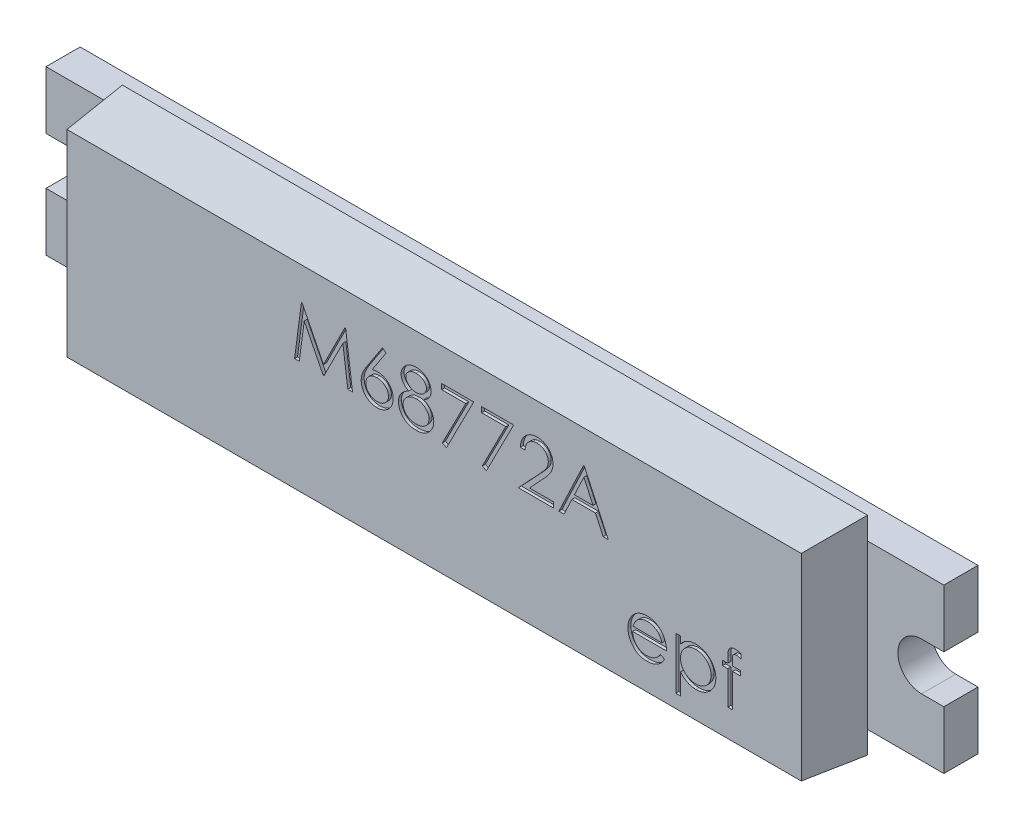
SolidWorks part; units mm, degrees
ref_plane "Alzado" through (0, 0, 0) normal (0, 0, 1) x (1, 0, 0)
ref_plane "Planta" through (0, 0, 0) normal (0, 1, 0) x (1, 0, 0)
ref_plane "Vista lateral" through (0, 0, 0) normal (1, 0, 0) x (0, 0, -1)
sketch "Croquis1" plane through (0, 0, 0) normal (0, 0, 1) x (1, 0, 0)
  line L1 (-30.25, -5.5) -> (30.25, -5.5)
  line L2 (-30.25, -5.5) -> (-30.25, 5.5)
  line L3 (-30.25, 5.5) -> (30.25, 5.5)
  line L4 (30.25, -5.5) -> (30.25, 5.5)
  line L5 (-30.25, -5.5) -> (30.25, 5.5) construction
  line L6 (-30.25, 5.5) -> (30.25, -5.5) construction
  point P0 (0, 0)
  dimension "D1" = 60.5
  dimension "D2" = 11
extrude "Saliente-Extruir1" add sketch "Croquis1" along normal blind 2.3
sketch "Croquis2" plane through (0, 0, 2.3) normal (0, 0, 1) x (1, 0, 0)
  line L0 (-38.0446, 0) -> (40.7787, 0) construction
  line L2 (-28.75, 1.6) -> (-31.5698, 1.6)
  line L3 (-28.75, -1.6) -> (-31.5698, -1.6)
  line L4 (-31.5698, 1.6) -> (-31.5698, -1.6)
  line L6 (28.75, 1.6) -> (32.3574, 1.6)
  line L7 (28.75, -1.6) -> (32.3574, -1.6)
  line L8 (32.3574, 1.6) -> (32.3574, -1.6)
  arc A0 (-28.75, -1.6) -> (-28.75, 1.6) centre (-28.75, 0) ccw
  arc A1 (28.75, 1.6) -> (28.75, -1.6) centre (28.75, 0) ccw
  dimension "D1" = 3.2
  dimension "D3" = 3.2
  dimension "D2" = 28.75
  dimension "D4" = 28.75
  dimension "D5" = 2.8198
  dimension "D6" = 3.6074
  dimension "D7" = 3.2
  dimension "D8" = 3.2
extrude "Cortar-Extruir1" cut sketch "Croquis2" against normal up to next
sketch "Croquis3" plane through (0, 0, 2.3) normal (0, 0, 1) x (1, 0, 0)
  line L1 (25.1, -7) -> (-25.1, -7)
  line L2 (25.1, -7) -> (25.1, 7)
  line L3 (25.1, 7) -> (-25.1, 7)
  line L4 (-25.1, -7) -> (-25.1, 7)
  line L5 (25.1, -7) -> (-25.1, 7) construction
  line L6 (25.1, 7) -> (-25.1, -7) construction
  point P0 (0, 0)
  dimension "D1" = 50.2
  dimension "D2" = 14
extrude "Saliente-Extruir2" add sketch "Croquis3" along normal blind 4.1 draft 5
sketch "Croquis6" plane through (-30.25, 0, 0) normal (-1, 0, 0) x (0, 0, 1)
  line L0 (0, 0) -> (0, -10) construction
  line L1 (0, 0) -> (3.4, 0) construction
  line L2 (0, -9) -> (0.2, -9) construction
  line L3 (0, -10) -> (0.2, -10)
  line L4 (0, -10) -> (0, -9)
  line L5 (3.4, -8) -> (3.6, -8) construction
  line L6 (0.2, -10) -> (0.2, -9.0748)
  line L7 (3.4, 0) -> (3.6, 0)
  line L8 (3.4, 0) -> (3.4, -7.9252)
  line L9 (3.4, -7.9252) -> (0.0718, -8.9041)
  line L10 (3.6, 0) -> (3.6, -8)
  line L11 (3.5282, -8.0959) -> (0.2, -9.0748)
  arc A0 (0.0718, -8.9041) -> (0, -9) centre (0.1, -9) ccw
  arc A1 (3.5282, -8.0959) -> (3.6, -8) centre (3.5, -8) ccw
  dimension "D1" = 3.4
  dimension "D2" = 10
  dimension "D3" = 0.2
  dimension "D4" = 1
  dimension "D5" = 8
  dimension "D6" = 0.2
extrude "Saliente-Extruir3" add sketch "Croquis6" along normal blind 0.2 from offset 8.3 offset against normal yes
sketch "Croquis7" plane through (-30.25, 0, 0) normal (-1, 0, 0) x (0, 0, 1)
  line L8 (3.6, -6.8863) -> (3.4, -6.9038)
  line L9 (3.4, -6.9038) -> (3.4, -7.9252)
  line L10 (3.4, -7.9252) -> (0.0718, -8.9041)
  line L11 (0, -9) -> (0, -10)
  line L12 (0, -10) -> (0.2, -10)
  line L13 (0.2, -10) -> (0.2, -9.0748)
  line L14 (0.2, -9.0748) -> (3.5282, -8.0959)
  line L15 (3.6, -8) -> (3.6, -6.8863)
  line L16 (3.6, -6.8863) -> (3.4, -6.9038)
  line L17 (3.4, -6.9038) -> (3.4, -7.9252)
  line L18 (3.4, -7.9252) -> (0.0718, -8.9041)
  line L19 (0, -9) -> (0, -10)
  line L20 (0, -10) -> (0.2, -10)
  line L21 (0.2, -10) -> (0.2, -9.0748)
  line L22 (0.2, -9.0748) -> (3.5282, -8.0959)
  line L23 (3.6, -8) -> (3.6, -6.8863)
  arc A2 (0.0718, -8.9041) -> (0, -9) centre (0.1, -9) ccw
  arc A3 (3.5282, -8.0959) -> (3.6, -8) centre (3.5, -8) ccw
  arc A4 (0.0718, -8.9041) -> (0, -9) centre (0.1, -9) ccw
  arc A5 (3.5282, -8.0959) -> (3.6, -8) centre (3.5, -8) ccw
  dimension "D1" = 0
extrude "Saliente-Extruir4" add sketch "Croquis7" along normal blind 0.2 from offset 21.3 offset against normal yes
sketch "Croquis8" plane through (-30.25, 0, 0) normal (-1, 0, 0) x (0, 0, 1)
  line L8 (3.6, -6.8863) -> (3.4, -6.9038)
  line L9 (3.4, -6.9038) -> (3.4, -7.9252)
  line L10 (3.4, -7.9252) -> (0.0718, -8.9041)
  line L11 (0, -9) -> (0, -10)
  line L12 (0, -10) -> (0.2, -10)
  line L13 (0.2, -10) -> (0.2, -9.0748)
  line L14 (0.2, -9.0748) -> (3.5282, -8.0959)
  line L15 (3.6, -8) -> (3.6, -6.8863)
  line L16 (3.6, -6.8863) -> (3.4, -6.9038)
  line L17 (3.4, -6.9038) -> (3.4, -7.9252)
  line L18 (3.4, -7.9252) -> (0.0718, -8.9041)
  line L19 (0, -9) -> (0, -10)
  line L20 (0, -10) -> (0.2, -10)
  line L21 (0.2, -10) -> (0.2, -9.0748)
  line L22 (0.2, -9.0748) -> (3.5282, -8.0959)
  line L23 (3.6, -8) -> (3.6, -6.8863)
  arc A2 (0.0718, -8.9041) -> (0, -9) centre (0.1, -9) ccw
  arc A3 (3.5282, -8.0959) -> (3.6, -8) centre (3.5, -8) ccw
  arc A4 (0.0718, -8.9041) -> (0, -9) centre (0.1, -9) ccw
  arc A5 (3.5282, -8.0959) -> (3.6, -8) centre (3.5, -8) ccw
  dimension "D1" = 0
extrude "Saliente-Extruir5" add sketch "Croquis8" along normal blind 0.2 from offset 43.3 offset against normal yes
sketch "Croquis9" plane through (-30.25, 0, 0) normal (-1, 0, 0) x (0, 0, 1)
  line L8 (3.6, -6.8863) -> (3.4, -6.9038)
  line L9 (3.4, -6.9038) -> (3.4, -7.9252)
  line L10 (3.4, -7.9252) -> (0.0718, -8.9041)
  line L11 (0, -9) -> (0, -10)
  line L12 (0, -10) -> (0.2, -10)
  line L13 (0.2, -10) -> (0.2, -9.0748)
  line L14 (0.2, -9.0748) -> (3.5282, -8.0959)
  line L15 (3.6, -8) -> (3.6, -6.8863)
  line L16 (3.6, -6.8863) -> (3.4, -6.9038)
  line L17 (3.4, -6.9038) -> (3.4, -7.9252)
  line L18 (3.4, -7.9252) -> (0.0718, -8.9041)
  line L19 (0, -9) -> (0, -10)
  line L20 (0, -10) -> (0.2, -10)
  line L21 (0.2, -10) -> (0.2, -9.0748)
  line L22 (0.2, -9.0748) -> (3.5282, -8.0959)
  line L23 (3.6, -8) -> (3.6, -6.8863)
  arc A2 (0.0718, -8.9041) -> (0, -9) centre (0.1, -9) ccw
  arc A3 (3.5282, -8.0959) -> (3.6, -8) centre (3.5, -8) ccw
  arc A4 (0.0718, -8.9041) -> (0, -9) centre (0.1, -9) ccw
  arc A5 (3.5282, -8.0959) -> (3.6, -8) centre (3.5, -8) ccw
  dimension "D1" = 0
extrude "Saliente-Extruir6" add sketch "Croquis9" along normal blind 0.2 from offset 51.3 separate body offset against normal yes
sketch "Croquis10" plane through (0, 0, 6.4) normal (0, 0, 1) x (1, 0, 0)
  text T0 "M68772A"
  text T1 "epf"
extrude "Cortar-Extruir2" cut sketch "Croquis10" against normal blind 0.2
